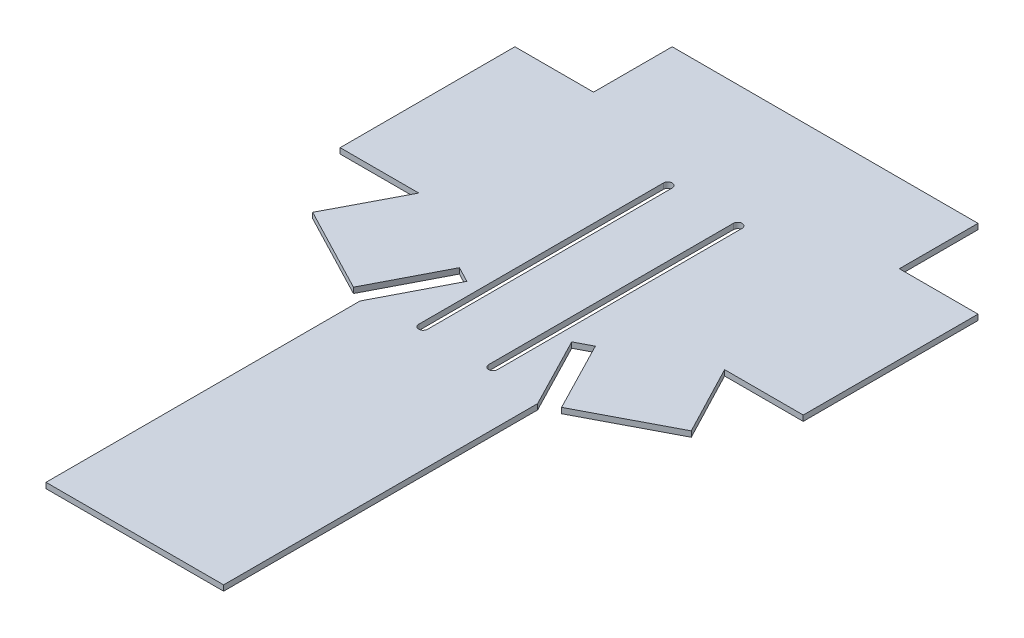
SolidWorks part; units mm, degrees
ref_plane "Front Plane" through (0, 0, 0) normal (0, 0, 1) x (1, 0, 0)
ref_plane "Top Plane" through (0, 0, 0) normal (0, 1, 0) x (1, 0, 0)
ref_plane "Right Plane" through (0, 0, 0) normal (1, 0, 0) x (0, 0, -1)
sketch "Sketch1" plane through (0, 0, 0) normal (0, 1, 0) x (1, 0, 0)
  line L0 (0, 0) -> (0, -300) construction
  line L1 (87.5, 0) -> (-87.5, 0)
  line L2 (-87.5, 0) -> (-87.5, -100)
  line L3 (-87.5, -100) -> (-30, -130)
  line L4 (-30, -130) -> (-30, -350)
  line L5 (-30, -350) -> (30, -350)
  line L6 (30, -130) -> (30, -350)
  line L7 (87.5, -100) -> (30, -130)
  line L8 (87.5, 0) -> (87.5, -100)
  point P9 (0, -350)
  dimension "D1" = 87.5
  dimension "D2" = 300
  dimension "D3" = 30
  dimension "100" = 100
  dimension "D4" = 30
  dimension "D5" = 250
extrude "Base" add sketch "Sketch1" along normal blind 3.175
sketch "Sketch2" plane through (0, 0, 0) normal (0, 1, 0) x (1, 0, 0)
  line L0 (-87.5, 0) -> (-87.5, -100) construction
  line L1 (87.5, 0) -> (-87.5, 0) construction
  line L2 (-87.5, 0) -> (-87.5, 45)
  line L3 (-87.5, 45) -> (87.5, 45)
  line L8 (-108.3155, -139.8963) -> (-87.5, -100)
  line L9 (-108.3155, -139.8963) -> (-59.5533, -165.3374)
  line L11 (-87.5, -100) -> (-30, -130) construction
  line L14 (0, 0) -> (0, -179.1679) construction
  line L18 (108.3155, -139.8963) -> (59.5533, -165.3374)
  line L19 (108.3155, -139.8963) -> (87.5, -100)
  line L20 (87.5, 0) -> (-87.5, 0)
  line L23 (87.5, 0) -> (87.5, 45)
  line L24 (-59.5533, -165.3374) -> (-38.7339, -125.039)
  line L25 (-87.5, -100) -> (-38.7339, -125.039)
  line L26 (87.5, -100) -> (38.7339, -125.039)
  line L27 (59.5533, -165.3374) -> (38.7339, -125.039)
  line L28 (-30, -130) -> (-50.8194, -170.2985)
  line L29 (-50.8194, -170.2985) -> (-50.8194, -350)
  line L30 (-50.8194, -350) -> (-30, -350)
  line L31 (-30, -130) -> (-30, -350)
  line L32 (50.8194, -170.2985) -> (50.8194, -350)
  line L33 (30, -130) -> (30, -350)
  line L34 (50.8194, -350) -> (30, -350)
  line L35 (30, -130) -> (50.8194, -170.2985)
  point P28 (0, 45)
  dimension "D1" = 55
extrude "Boss-Extrude2" add sketch "Sketch2" along normal blind 3.175
sketch "Sketch3" plane through (0, 0, 0) normal (0, 1, 0) x (1, 0, 0)
  line L0 (-87.5, -100) -> (-132.5, -100)
  line L1 (-132.5, -100) -> (-132.5, 0)
  line L2 (-132.5, 0) -> (-87.5, 0)
  line L3 (-87.5, 45) -> (-87.5, -100) construction
  line L5 (-87.5, 0) -> (-87.5, -100)
  line L6 (0, 0) -> (0, -126.794) construction
  line L7 (87.5, 0) -> (87.5, -100)
  line L8 (132.5, 0) -> (87.5, 0)
  line L9 (132.5, -100) -> (132.5, 0)
  line L10 (87.5, -100) -> (132.5, -100)
  dimension "D1" = 45
extrude "Boss-Extrude3" add sketch "Sketch3" along normal blind 3.175
sketch "Sketch4" plane through (0, 3.175, 0) normal (0, 1, 0) x (1, 0, 0)
  line L0 (-30, -130) -> (-30, -350) construction
  line L1 (-50.8194, -350) -> (50.8194, -350) construction
  line L2 (30, -350) -> (30, 45) construction
  line L3 (87.5, 45) -> (-87.5, 45) construction
  line L4 (30, 45) -> (-30, 45) construction
  line L5 (-30, 45) -> (-30, -130) construction
  line L6 (-20, -25) -> (-20, -165) construction
  line L7 (-17.5, -25) -> (-17.5, -165)
  line L8 (-22.5, -25) -> (-22.5, -165)
  line L10 (0, 0) -> (0, -161.3627) construction
  line L11 (20, -25) -> (20, -165) construction
  line L12 (17.5, -25) -> (17.5, -165)
  line L13 (22.5, -25) -> (22.5, -165)
  arc A0 (-17.5, -25) -> (-22.5, -25) centre (-20, -25) ccw
  arc A1 (-22.5, -165) -> (-17.5, -165) centre (-20, -165) ccw
  arc A2 (17.5, -25) -> (22.5, -25) centre (20, -25) cw
  arc A3 (22.5, -165) -> (17.5, -165) centre (20, -165) cw
  point P13 (-20, -95)
  point P23 (20, -95)
  dimension "D1" = 2.5
  dimension "D2" = 15
  dimension "D3" = 25
  dimension "D4" = 140
extrude "Cut-Extrude1" cut sketch "Sketch4" against normal through all
